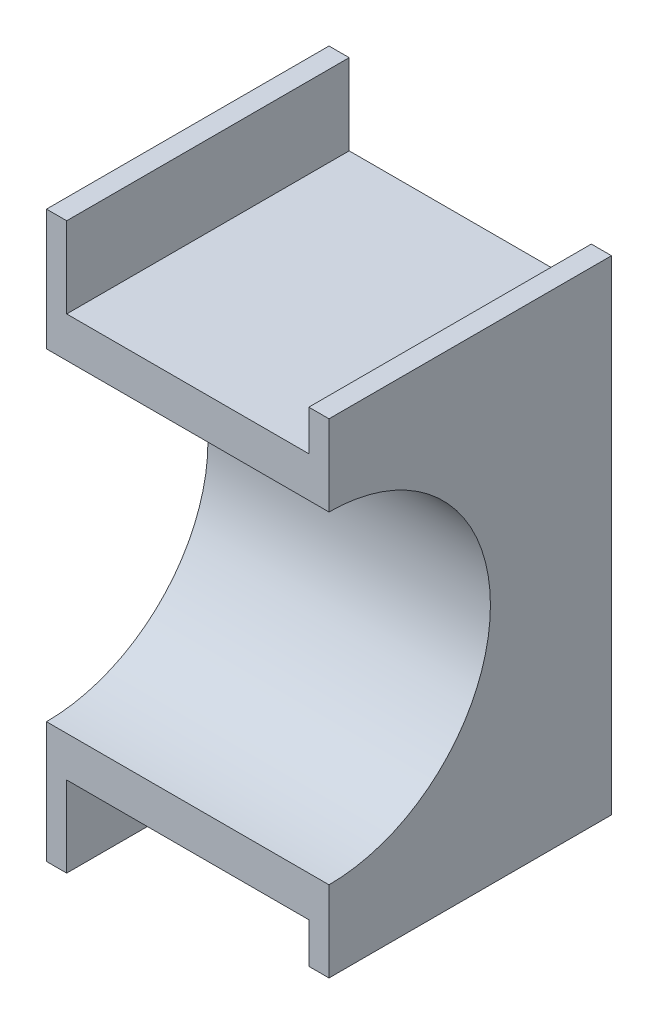
SolidWorks part; units mm, degrees
ref_plane "Plan de face" through (0, 0, 0) normal (0, 0, 1) x (1, 0, 0)
ref_plane "Plan de dessus" through (0, 0, 0) normal (0, 1, 0) x (1, 0, 0)
ref_plane "Plan de droite" through (0, 0, 0) normal (1, 0, 0) x (0, 0, -1)
sketch "Esquisse1" plane through (0, 0, 0) normal (0, 0, 1) x (1, 0, 0)
  line L1 (-1.5, 3.5) -> (2, 3.5)
  line L2 (-1.5, 3.5) -> (-1.5, -3.5)
  line L3 (-1.5, -3.5) -> (2, -3.5)
  line L4 (2, 3.5) -> (2, -3.5)
  dimension "D1" = 1.5
  dimension "D2" = 2
  dimension "D3" = 3.5
  dimension "D4" = 3.5
extrude "Boss.-Extru.1" add sketch "Esquisse1" along normal blind 3.5
sketch "Esquisse2" plane through (0, 3.5, 0) normal (0, 1, 0) x (1, 0, 0)
  line L0 (2, 0) -> (-1.5, 0) construction
  line L1 (-1.25, 0) -> (1.75, 0)
  line L2 (-1.25, 0) -> (-1.25, -3.5)
  line L3 (-1.25, -3.5) -> (1.75, -3.5)
  line L4 (1.75, 0) -> (1.75, -3.5)
  line L5 (2, -3.5) -> (-1.5, -3.5) construction
  line L6 (-1.5, -3.5) -> (-1.5, 0) construction
  dimension "D1" = 3
  dimension "D2" = 0.25
extrude "Enlèv. mat.-Extru.1" cut sketch "Esquisse2" against normal blind 1 contours L2 L1 L4 L3
sketch "Esquisse3" plane through (0, -3.5, 0) normal (0, -1, 0) x (-1, 0, 0)
  line L0 (1.5, 0) -> (-2, 0) construction
  line L1 (-1.75, 0) -> (1.25, 0)
  line L2 (-1.75, 0) -> (-1.75, -3.5)
  line L3 (-1.75, -3.5) -> (1.25, -3.5)
  line L4 (1.25, 0) -> (1.25, -3.5)
  line L5 (1.5, -3.5) -> (-2, -3.5) construction
  line L6 (-2, -3.5) -> (-2, 0) construction
  dimension "D1" = 0.25
  dimension "D2" = 3
extrude "Enlèv. mat.-Extru.2" cut sketch "Esquisse3" against normal blind 1 contours L2 L1 L4 L3
sketch "Esquisse5" plane through (2, 0, 0) normal (1, 0, 0) x (0, 0, -1)
  line L0 (-3.5, -3.5) -> (-3.5, 3.5) construction
  line L1 (-3.5, -2) -> (-3.5, 2)
  arc A0 (-3.5, -2) -> (-3.5, 2) centre (-3.5, 0) ccw
  dimension "D1" = 2
extrude "Enlèv. mat.-Extru.4" cut sketch "Esquisse5" against normal blind 10 contours L1 A0
sketch "Esquisse6" plane through (2, 0, 0) normal (1, 0, 0) x (0, 0, -1)
  line L6 (-3.5, 2) -> (-3.5, 3.5) construction
  line L7 (0, 3.5) -> (-3.5, 3.5)
  line L8 (0, 3.5) -> (0, 3)
  line L9 (0, 3) -> (-3.5, 3)
  line L10 (-3.5, 3.5) -> (-3.5, 3)
  line L11 (0, -3.5) -> (0, 3.5) construction
  line L12 (-3.5, -3.5) -> (0, -3.5)
  line L13 (-3.5, -3.5) -> (-3.5, -3)
  line L14 (-3.5, -3) -> (0, -3)
  line L15 (0, -3.5) -> (0, -3)
  dimension "D1" = 0.5
  dimension "D4" = 0.5
extrude "Enlèv. mat.-Extru.5" cut sketch "Esquisse6" against normal blind 2
